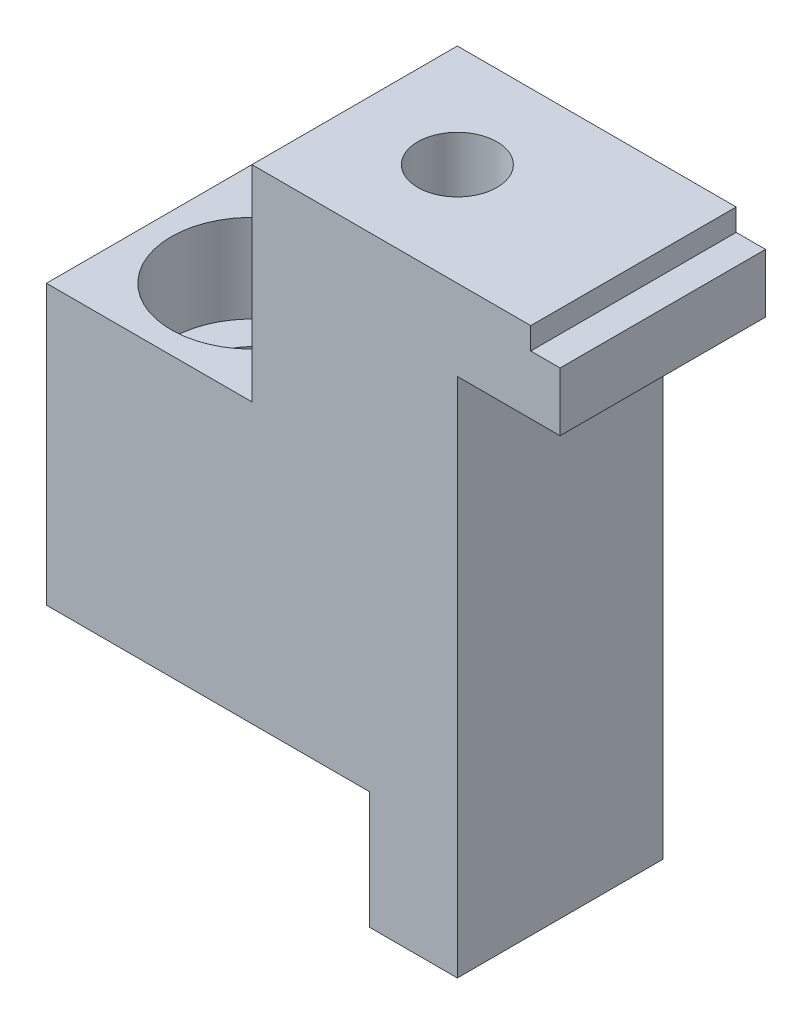
SolidWorks part; units mm, degrees
ref_plane "Alzado" through (0, 0, 0) normal (0, 0, 1) x (1, 0, 0)
ref_plane "Planta" through (0, 0, 0) normal (0, 1, 0) x (1, 0, 0)
ref_plane "Vista lateral" through (0, 0, 0) normal (1, 0, 0) x (0, 0, -1)
sketch "Croquis1" plane through (0, 0, 0) normal (0, 0, 1) x (1, 0, 0)
  line L0 (10.5, 15.75) -> (10.5, 16.25) construction
  line L1 (0, 0) -> (4, 0)
  line L2 (0, 9.5) -> (0, 16.5)
  line L4 (7, 0) -> (7, 13.75)
  line L9 (9.5, 15.75) -> (10.5, 15.75)
  line L12 (10.5, 15.75) -> (10.5, 13.75)
  line L13 (10.5, 16) -> (7, 16) construction
  line L15 (7, 13.75) -> (7, 16.5) construction
  line L16 (0, 9.5) -> (0, 0) construction
  line L17 (3.5, 0) -> (3.5, 16.5) construction
  line L18 (7, 16.5) -> (0, 16.5)
  line L21 (7, 16.5) -> (9.5, 16.5)
  line L22 (9.5, 15.75) -> (9.5, 16.5)
  line L25 (7, 13.75) -> (10.5, 13.75)
  line L27 (0, 0) -> (-7, 0)
  line L29 (0, 9.5) -> (-7, 9.5)
  line L30 (-7, 0) -> (-7, 9.5)
  line L31 (-3.5, 9.5) -> (-3.5, 0) construction
  line L32 (4, 0) -> (7, 0) construction
  line L34 (7, 0) -> (7, -4)
  line L35 (7, -4) -> (4, -4)
  line L36 (4, 0) -> (4, -4)
  line L37 (0, 13) -> (3.5, 13) construction
  line L38 (3.5, 13) -> (7, 13) construction
  dimension "D1" = 16.5
  dimension "D2" = 7
  dimension "D3" = 0.5
  dimension "D4" = 16
  dimension "D5" = 2
  dimension "D6" = 7
  dimension "D7" = 1
  dimension "D8" = 9.5
  dimension "D9" = 7
  dimension "D10" = 7.5
  dimension "D11" = 4
extrude "Saliente-Extruir1" add sketch "Croquis1" along normal blind 7
sketch "Croquis4" plane through (0, 16.5, 0) normal (0, 1, 0) x (1, 0, 0)
  line L0 (0, 0) -> (7, -7) construction
  line L1 (7, -7) -> (7, 0) construction
  line L2 (9.5, -7) -> (0, -7) construction
  circle A0 centre (3.5, -3.5) radius 1.35
  dimension "D1" = 2.7
extrude "Cortar-Extruir1" cut sketch "Croquis4" against normal blind 13.5
sketch "Croquis5" plane through (0, 9.5, 0) normal (0, 1, 0) x (1, 0, 0)
  line L0 (-7, 0) -> (0, -7) construction
  circle A0 centre (-3.5, -3.5) radius 1.6
  dimension "D1" = 3.2
extrude "Cortar-Extruir2" cut sketch "Croquis5" against normal blind 13.9
sketch "Croquis6" plane through (0, 9.5, 0) normal (0, 1, 0) x (1, 0, 0)
  circle A0 centre (-3.5, -3.5) radius 2.75
  dimension "D1" = 5.5
extrude "Cortar-Extruir3" cut sketch "Croquis6" against normal blind 3
